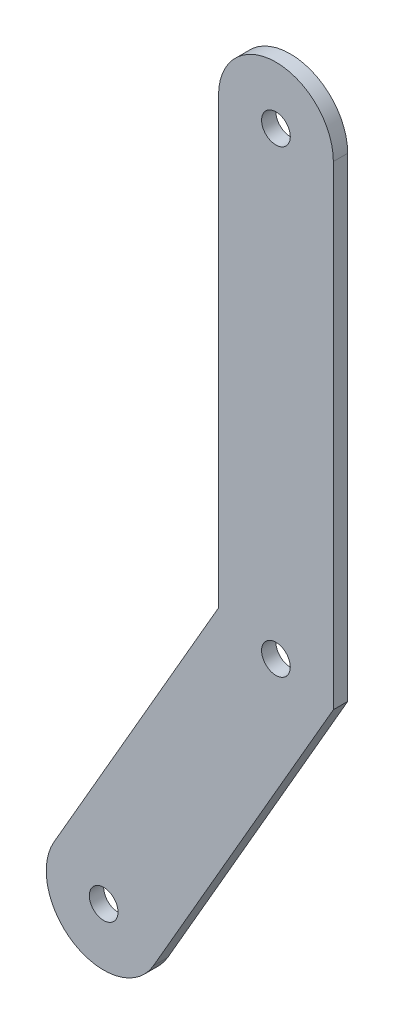
SolidWorks part; units mm, degrees
material "5052-H32"
ref_plane "Front Plane" through (0, 0, 0) normal (0, 0, 1) x (1, 0, 0)
ref_plane "Top Plane" through (0, 0, 0) normal (0, 1, 0) x (1, 0, 0)
ref_plane "Right Plane" through (0, 0, 0) normal (1, 0, 0) x (0, 0, -1)
sketch "Sketch1" plane through (0, 0, 0) normal (0, 0, 1) x (1, 0, 0)
  line L2 (-108.4059, -695.7645) -> (50.8, -420.0118)
  line L5 (50.8, -420.0118) -> (50.8, 0)
  line L6 (-50.8, 0) -> (-50.8, -392.7882)
  line L7 (-50.8, -392.7882) -> (-196.3941, -644.9645)
  line L8 (-152.4, -670.3645) -> (0, -406.4) construction
  line L9 (0, -406.4) -> (0, 0) construction
  line L10 (-50.8, -392.7882) -> (0, -406.4) construction
  line L11 (0, -406.4) -> (50.8, -420.0118) construction
  line L12 (-108.4059, -695.7645) -> (-268.2355, -1010.3745) construction
  line L14 (-358.7518, -964.39) -> (-197.6906, -647.3558) construction
  arc A6 (50.8, 0) -> (-50.8, 0) centre (0, 0) ccw
  arc A7 (-196.3941, -644.9645) -> (-108.4059, -695.7645) centre (-152.4, -670.3645) ccw
  circle A8 centre (0, 0) radius 12.7
  circle A9 centre (-152.4, -670.3645) radius 12.7
  circle A10 centre (0, -406.4) radius 12.7
  arc A11 (-358.7518, -964.39) -> (-268.2355, -1010.3745) centre (-313.4936, -987.3822) ccw construction
  arc A12 (-197.6906, -647.3558) -> (-196.3941, -644.9645) centre (-152.4, -670.3645) cw construction
  point P16 (-203.2, -845.3521)
  point P18 (-108.4059, -1000.4263)
  point P20 (0, 0)
  point P21 (0, 0)
  point P22 (0, 0)
  point P23 (-227.9451, -992.0679)
  dimension "D1" = 101.6
  dimension "D3" = 150
  dimension "D4" = 304.8
  dimension "D5" = 304.8
  dimension "D2" = 25.4
  dimension "D6" = 406.4
  dimension "D7" = 355.6
  dimension "D8" = 176.932
extrude "Boss-Extrude1" add sketch "Sketch1" along normal blind 12.7
